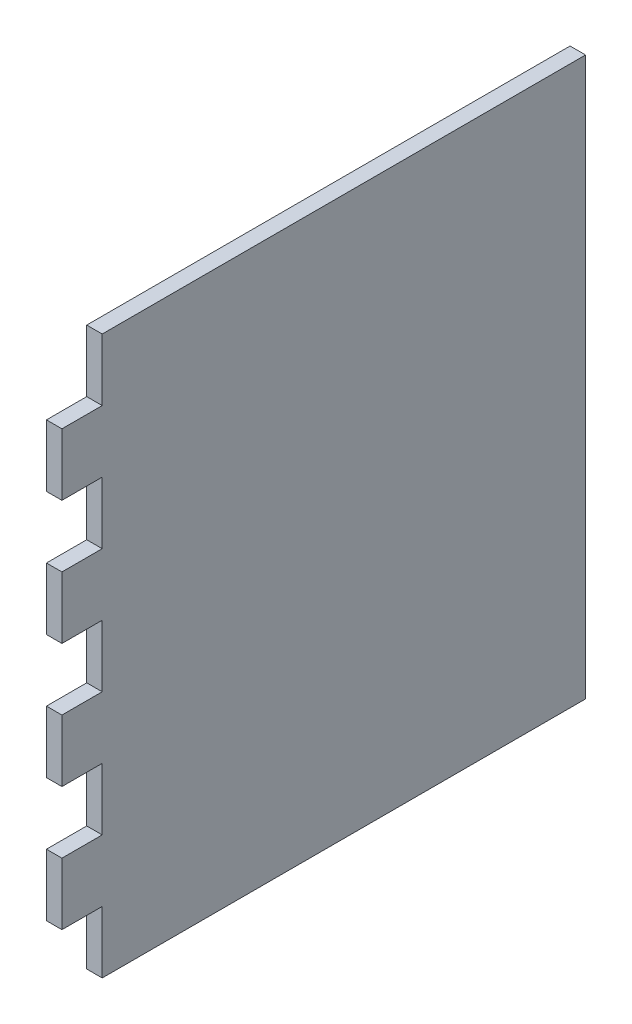
SolidWorks part; units mm, degrees
ref_plane "Front Plane" through (0, 0, 0) normal (0, 0, 1) x (1, 0, 0)
ref_plane "Top Plane" through (0, 0, 0) normal (0, 1, 0) x (1, 0, 0)
ref_plane "Right Plane" through (0, 0, 0) normal (1, 0, 0) x (0, 0, -1)
sketch "Sketch2" plane through (0, 0, 0) normal (1, 0, 0) x (0, 0, -1)
  line L0 (-115.57, 38.1) -> (-115.57, 12.7)
  line L1 (-99.06, -114.3) -> (99.06, -114.3)
  line L2 (-99.06, -114.3) -> (-99.06, -88.9)
  line L3 (-99.06, 114.3) -> (99.06, 114.3)
  line L4 (99.06, -114.3) -> (99.06, 114.3)
  line L5 (-99.06, -114.3) -> (99.06, 114.3) construction
  line L6 (-99.06, 114.3) -> (99.06, -114.3) construction
  line L7 (-99.06, 88.9) -> (-115.57, 88.9)
  line L9 (-99.06, 63.5) -> (-115.57, 63.5)
  line L10 (-115.57, 88.9) -> (-115.57, 63.5)
  line L11 (-99.06, 38.1) -> (-115.57, 38.1)
  line L12 (-99.06, 12.7) -> (-115.57, 12.7)
  line L13 (-115.57, -12.7) -> (-115.57, -38.1)
  line L14 (-99.06, -12.7) -> (-115.57, -12.7)
  line L15 (-99.06, -38.1) -> (-115.57, -38.1)
  line L16 (-115.57, -63.5) -> (-115.57, -88.9)
  line L17 (-99.06, -63.5) -> (-115.57, -63.5)
  line L18 (-99.06, -88.9) -> (-115.57, -88.9)
  line L19 (-99.06, 88.9) -> (-99.06, 114.3)
  line L20 (-99.06, 38.1) -> (-99.06, 63.5)
  line L21 (-99.06, -12.7) -> (-99.06, 12.7)
  line L22 (-99.06, -63.5) -> (-99.06, -38.1)
  point P0 (0, 0)
  dimension "D1" = 228.6
  dimension "D2" = 25.4
  dimension "D3" = 25.4
  dimension "D4" = 16.51
  dimension "D6" = 198.12
  dimension "D5" = 4
extrude "Boss-Extrude1" add sketch "Sketch2" along normal blind 6.35
